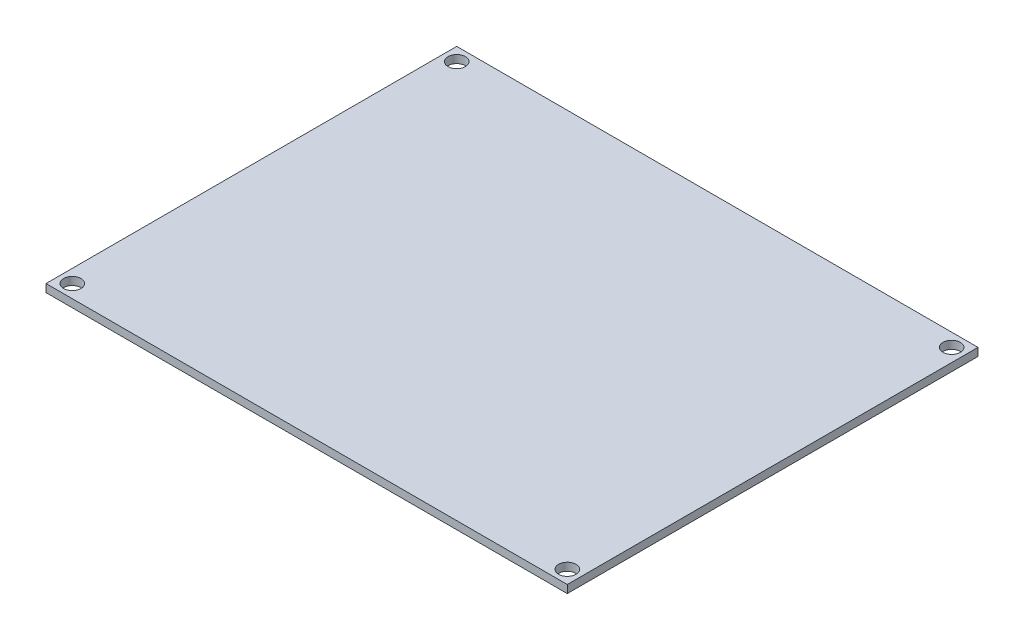
SolidWorks part; units mm, degrees
ref_plane "Front Plane" through (0, 0, 0) normal (0, 0, 1) x (1, 0, 0)
ref_plane "Top Plane" through (0, 0, 0) normal (0, 1, 0) x (1, 0, 0)
ref_plane "Right Plane" through (0, 0, 0) normal (1, 0, 0) x (0, 0, -1)
sketch "Sketch1" plane through (0, 0, 0) normal (0, 1, 0) x (1, 0, 0)
  line L1 (-49.5, -39) -> (49.5, -39)
  line L2 (-49.5, -39) -> (-49.5, 39)
  line L3 (-49.5, 39) -> (49.5, 39)
  line L4 (49.5, -39) -> (49.5, 39)
  line L5 (-49.5, -39) -> (49.5, 39) construction
  line L6 (-49.5, 39) -> (49.5, -39) construction
  point P0 (0, 0)
  dimension "D1" = 99
  dimension "D2" = 78
extrude "Boss-Extrude1" add sketch "Sketch1" along normal blind 1.5
sketch "Sketch2" plane through (0, 1.5, 0) normal (0, 1, 0) x (1, 0, 0)
  line L1 (-47, -36.5) -> (47, -36.5) construction
  line L2 (-47, -36.5) -> (-47, 36.5) construction
  line L3 (-47, 36.5) -> (47, 36.5) construction
  line L4 (47, -36.5) -> (47, 36.5) construction
  line L5 (-47, -36.5) -> (47, 36.5) construction
  line L6 (-47, 36.5) -> (47, -36.5) construction
  circle A0 centre (-47, 36.5) radius 1.65
  circle A1 centre (47, 36.5) radius 1.65
  circle A2 centre (47, -36.5) radius 1.65
  circle A3 centre (-47, -36.5) radius 1.65
  point P0 (0, 0)
  dimension "D3" = 3.3
  dimension "D1" = 94
  dimension "D2" = 73
extrude "Cut-Extrude1" cut sketch "Sketch2" against normal through all
